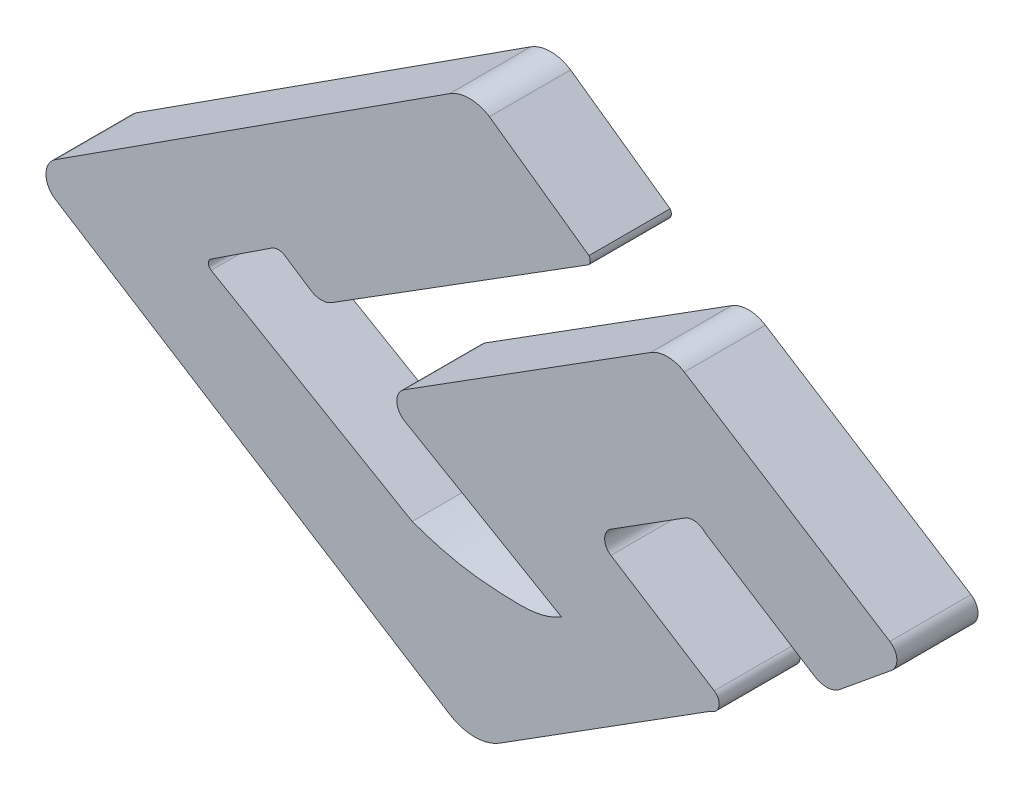
SolidWorks part; units mm, degrees
ref_plane "Front" through (0, 0, 0) normal (0, 0, 1) x (1, 0, 0)
ref_plane "Top" through (0, 0, 0) normal (0, 1, 0) x (1, 0, 0)
ref_plane "Right" through (0, 0, 0) normal (1, 0, 0) x (0, 0, -1)
sketch "草图1" plane through (0, 0, 0) normal (0, 0, 1) x (1, 0, 0)
  line L0 (37.6667, 113) -> (188.3333, 113) construction
  line B0 (47.5115, 142.0331) -> (110.6389, 102.2078)
  line B1 (118.6926, 102.208) -> (152.5218, 123.5526)
  line B2 (136.4891, 137.1659) -> (153.0489, 126.6498)
  line B3 (136.4944, 140.7979) -> (148.3346, 148.2685)
  line B4 (151.6184, 147.8262) -> (169.1219, 136.7108)
  line B5 (172.9459, 136.7108) -> (181.186, 143.4638)
  line B6 (148.253, 168.4865) -> (181.186, 147.5728)
  line B7 (142.8457, 168.4944) -> (103.3704, 143.5873)
  line B8 (103.3704, 139.328) -> (128.5569, 124.6724)
  line B9 (72.4525, 144.6962) -> (104.6594, 125.9554)
  line B10 (72.4106, 146.2361) -> (82.1499, 152.6362)
  line B11 (84.2658, 152.6357) -> (88.4029, 149.914)
  line B12 (91.7742, 149.8779) -> (132.9073, 175.6906)
  line B13 (132.9808, 177.0056) -> (117.0315, 188.3031)
  line B14 (47.4838, 147.573) -> (110.639, 188.3031)
  arc B15 (110.639, 188.3031) -> (117.0315, 188.3031) centre (113.8353, 183.347) cw
  arc B16 (47.4838, 147.573) -> (47.5115, 142.0331) centre (49.2645, 144.8119) ccw
  arc B17 (110.6389, 102.2078) -> (118.6926, 102.208) centre (114.6656, 108.5905) ccw
  arc B18 (153.0489, 126.6498) -> (152.5218, 123.5526) centre (152.1357, 125.2117) cw
  arc B19 (136.4944, 140.7979) -> (136.4891, 137.1659) centre (137.6413, 138.9802) ccw
  arc B20 (148.3346, 148.2685) -> (151.6184, 147.8262) centre (149.7122, 146.0851) cw
  arc B21 (169.1219, 136.7108) -> (172.9459, 136.7108) centre (171.0339, 139.7217) ccw
  arc B22 (181.186, 147.5728) -> (181.186, 143.4638) centre (179.8813, 145.5183) cw
  arc B23 (142.8457, 168.4944) -> (148.253, 168.4865) centre (145.5432, 164.2192) cw
  arc B24 (103.3704, 143.5873) -> (103.3704, 139.328) centre (104.7141, 141.4577) ccw
  arc B25 (132.9808, 177.0056) -> (132.9073, 175.6906) centre (132.1589, 176.392) cw
  arc B26 (88.4029, 149.914) -> (91.7742, 149.8779) centre (90.1167, 152.5191) ccw
  arc B27 (82.1499, 152.6362) -> (84.2658, 152.6357) centre (83.2074, 151.0269) cw
  arc B28 (72.4106, 146.2361) -> (72.4525, 144.6962) centre (72.9081, 145.4791) ccw
  spline B29 degree 3 poles (104.6594, 125.9554) (107.6306, 124.9006) (112.43, 123.5189) (120.558, 122.941) (125.6792, 122.8475) (128.5569, 124.6724) knots 0 0 0 0 0.387587 0.604017 1 1 1 1
sketch_block_instance "块1-1"
sketch_block "块1"
extrude "凸台-拉伸1" add sketch "草图1" along normal blind 13
